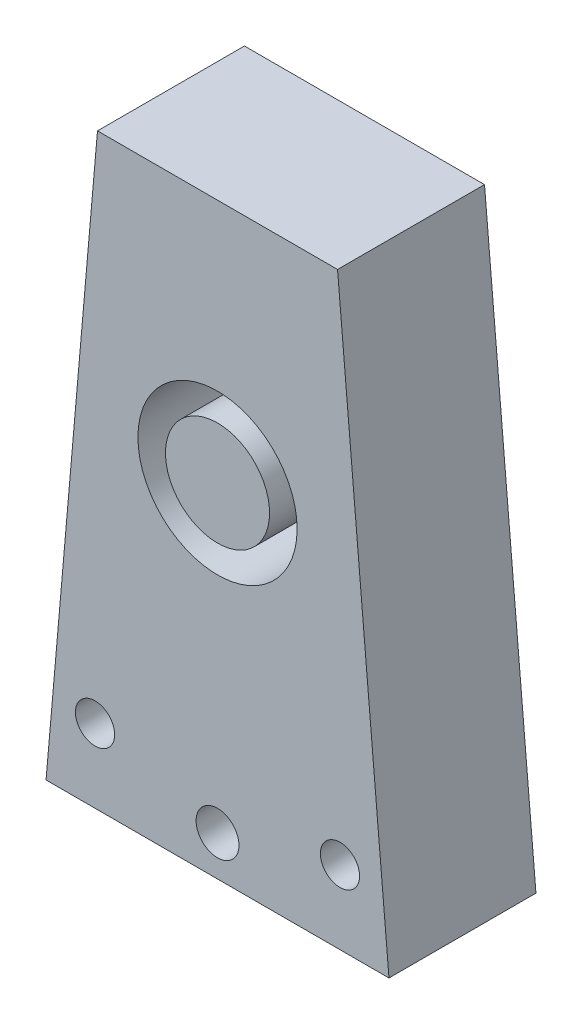
SolidWorks part; units mm, degrees
ref_plane "Front Plane" through (0, 0, 0) normal (0, 0, 1) x (1, 0, 0)
ref_plane "Top Plane" through (0, 0, 0) normal (0, 1, 0) x (1, 0, 0)
ref_plane "Right Plane" through (0, 0, 0) normal (1, 0, 0) x (0, 0, -1)
sketch "Sketch1" plane through (0, 0, 0) normal (0, 0, 1) x (1, 0, 0)
  line L0 (-14, 0) -> (14, 0)
  line L1 (14, 0) -> (9.8, 48)
  line L2 (9.8, 48) -> (-9.8, 48)
  line L3 (-9.8, 48) -> (-14, 0)
extrude "Boss-Extrude1" add sketch "Sketch1" along normal blind 12
sketch "Sketch2" plane through (0, 0, 0) normal (0, 0, 1) x (1, 0, 0)
  circle A0 centre (0, 28) radius 4.25
  circle A1 centre (10, 6) radius 1.6
  circle A2 centre (-10, 6) radius 1.6
  circle A3 centre (0, 52.75) radius 1.75
  circle A4 centre (0, 3.25) radius 1.75
  circle A5 centre (0, 28) radius 6.5
extrude "Cut-Extrude2" cut sketch "Sketch2" along normal blind 13
